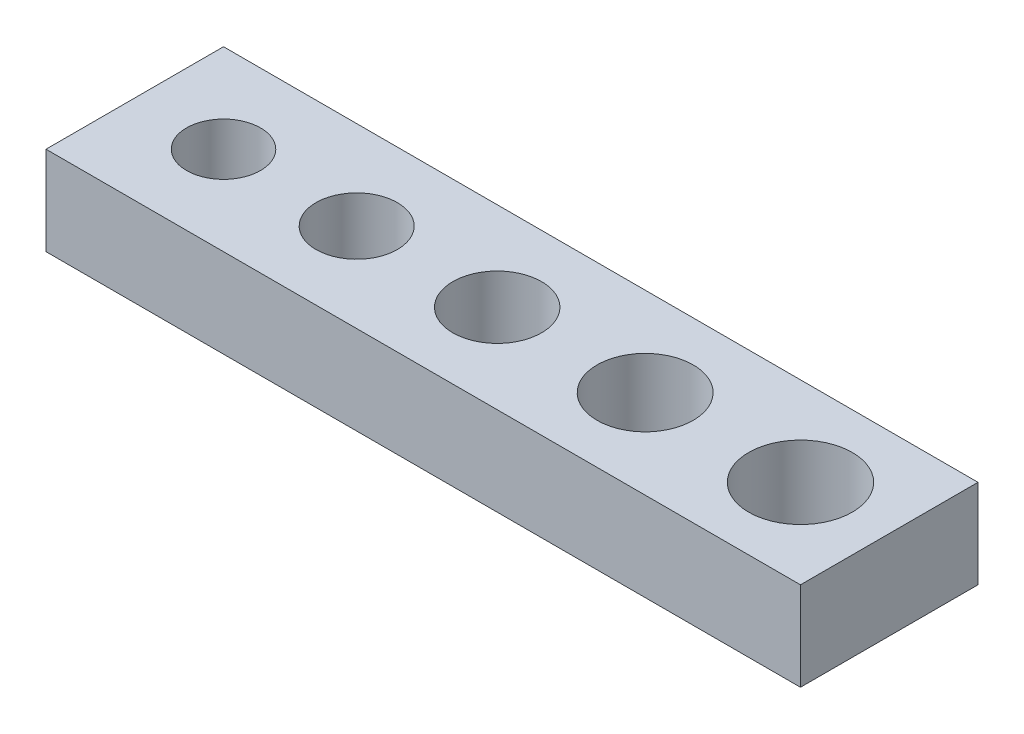
SolidWorks part; units mm, degrees
ref_plane "Front Plane" through (0, 0, 0) normal (0, 0, 1) x (1, 0, 0)
ref_plane "Top Plane" through (0, 0, 0) normal (0, 1, 0) x (1, 0, 0)
ref_plane "Right Plane" through (0, 0, 0) normal (1, 0, 0) x (0, 0, -1)
sketch "Sketch1" plane through (0, 0, 0) normal (0, 1, 0) x (1, 0, 0)
  line L0 (-19.5, 0) -> (0, 0) construction
  line L2 (-22.5, 3) -> (3, 3)
  line L3 (-22.5, 3) -> (-22.5, -3)
  line L4 (-22.5, -3) -> (3, -3)
  line L5 (3, 3) -> (3, -3)
  line L6 (-22.5, 3) -> (3, -3) construction
  line L7 (-22.5, -3) -> (3, 3) construction
  circle A0 centre (-19.5, 0) radius 1.25
  circle A1 centre (-10.25, 0) radius 1.5
  circle A2 centre (-5.25, 0) radius 1.625
  circle A3 centre (-15, 0) radius 1.375
  circle A4 centre (0, 0) radius 1.75
  point P10 (-9.75, 0)
  point P15 (3, 0)
  dimension "D1" = 2.5
  dimension "D2" = 3
  dimension "D3" = 3.25
  dimension "D4" = 2.75
  dimension "D5" = 3.5
  dimension "D6" = 4.5
  dimension "D10" = 3
  dimension "D7" = 4.75
  dimension "D8" = 5
  dimension "D9" = 5.25
  dimension "D11" = 3
extrude "Boss-Extrude1" add sketch "Sketch1" along normal blind 3
